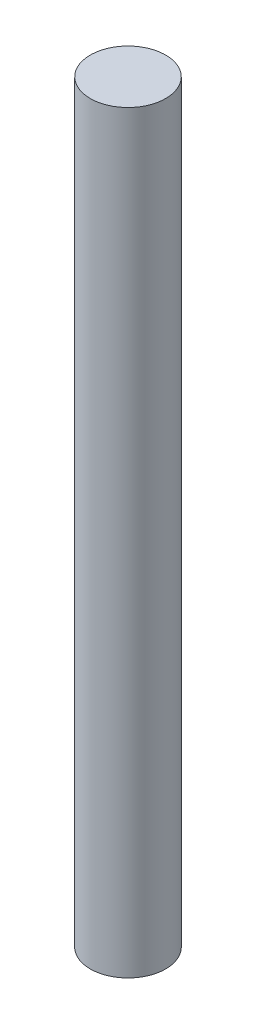
SolidWorks part; units mm, degrees
ref_plane "前视基准面" through (0, 0, 0) normal (0, 0, 1) x (1, 0, 0)
ref_plane "上视基准面" through (0, 0, 0) normal (0, 1, 0) x (1, 0, 0)
ref_plane "右视基准面" through (0, 0, 0) normal (1, 0, 0) x (0, 0, -1)
other "Configuration Table"
sketch "草图1" plane through (0, 0, 0) normal (0, 1, 0) x (1, 0, 0)
  circle A0 centre (0, 0) radius 5
extrude "凸台-拉伸1" add sketch "草图1" along normal blind 100
